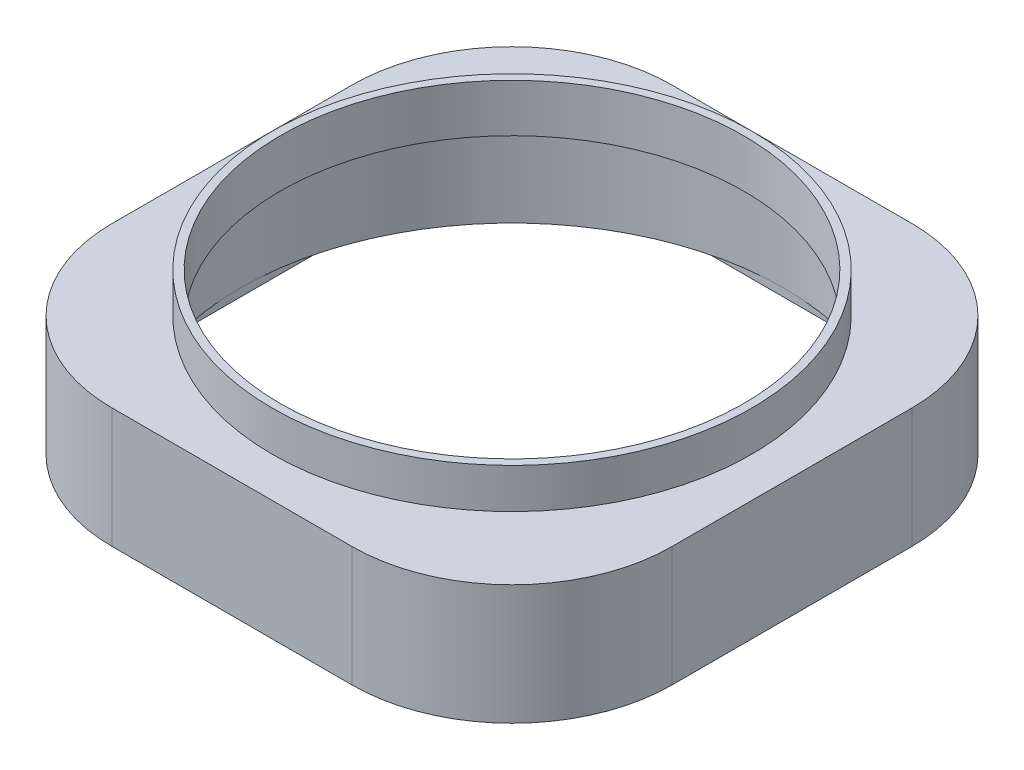
SolidWorks part; units mm, degrees
ref_plane "Front Plane" through (0, 0, 0) normal (0, 0, 1) x (1, 0, 0)
ref_plane "Top Plane" through (0, 0, 0) normal (0, 1, 0) x (1, 0, 0)
ref_plane "Right Plane" through (0, 0, 0) normal (1, 0, 0) x (0, 0, -1)
sketch "Sketch1" plane through (0, 0, 0) normal (0, 1, 0) x (1, 0, 0)
  line L1 (-30, 70) -> (30, 70)
  line L2 (-70, 30) -> (-70, -30)
  line L3 (-30, -70) -> (30, -70)
  line L4 (70, 30) -> (70, -30)
  arc A0 (-30, -70) -> (-70, -30) centre (-30, -30) cw
  arc A1 (30, -70) -> (70, -30) centre (30, -30) ccw
  arc A2 (70, 30) -> (30, 70) centre (30, 30) ccw
  arc A3 (-70, 30) -> (-30, 70) centre (-30, 30) cw
  dimension "D1" = 40
extrude "Boss-Extrude1" add sketch "Sketch1" against normal blind 40
sketch "Sketch2" plane through (0, 0, 0) normal (0, 1, 0) x (1, 0, 0)
  circle A0 centre (0, 0) radius 60
extrude "Boss-Extrude2" add sketch "Sketch2" along normal blind 10
sketch "Sketch3" plane through (0, 10, 0) normal (0, 1, 0) x (1, 0, 0)
  circle A0 centre (0, 0) radius 58
extrude "Cut-Extrude1" cut sketch "Sketch3" against normal blind 12
sketch "Sketch5" plane through (0, -40, 0) normal (0, -1, 0) x (1, 0, 0)
  circle A4 centre (0, 0) radius 68
extrude "Cut-Extrude3" cut sketch "Sketch5" against normal blind 38 contours A4
sketch "Sketch7" plane through (0, -40, 0) normal (0, -1, 0) x (1, 0, 0)
  line L1 (-76.7006, 70.9928) -> (75.7255, 70.9928)
  line L2 (-76.7006, 70.9928) -> (-76.7006, -73.7242)
  line L3 (-76.7006, -73.7242) -> (75.7255, -73.7242)
  line L4 (75.7255, 70.9928) -> (75.7255, -73.7242)
extrude "Cut-Extrude4" cut sketch "Sketch7" against normal blind 10
sketch "Sketch8" plane through (0, -30, 0) normal (0, -1, 0) x (1, 0, 0)
  line L5 (68, 30) -> (68, -30)
  line L6 (-30, 68) -> (30, 68)
  line L7 (-68, -30) -> (-68, 30)
  line L8 (30, -68) -> (-30, -68)
  arc A4 (68, 30) -> (30, 68) centre (30, 30) ccw
  arc A5 (-30, 68) -> (-68, 30) centre (-30, 30) ccw
  arc A6 (-68, -30) -> (-30, -68) centre (-30, -30) ccw
  arc A7 (30, -68) -> (68, -30) centre (30, -30) ccw
  point P24 (0, 0)
extrude "Cut-Extrude6" cut sketch "Sketch8" against normal blind 2
